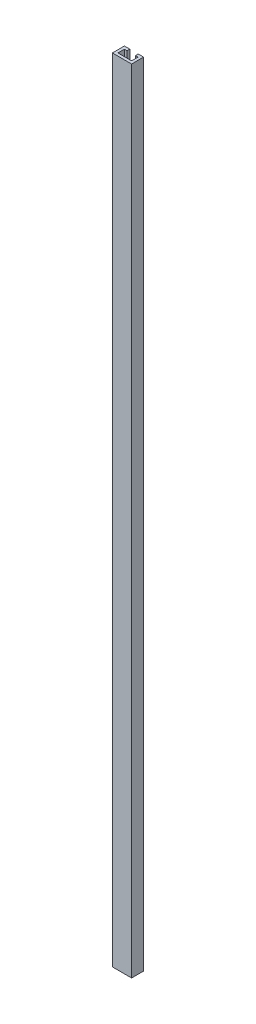
SolidWorks part; units mm, degrees
ref_plane "前视基准面" through (0, 0, 0) normal (0, 0, 1) x (1, 0, 0)
ref_plane "上视基准面" through (0, 0, 0) normal (0, 1, 0) x (1, 0, 0)
ref_plane "右视基准面" through (0, 0, 0) normal (1, 0, 0) x (0, 0, -1)
sketch "草图1" plane through (0, 0, 0) normal (0, 1, 0) x (1, 0, 0)
  line L0 (0, -5) -> (8, -5)
  line L1 (8, -5) -> (8, 0)
  line L2 (8, 0) -> (5.75, 0)
  line L3 (5.75, 0) -> (5.75, -1.15)
  line L4 (5.75, -1.15) -> (6.85, -1.15)
  line L5 (6.85, -1.15) -> (6.85, -3.85)
  line L6 (6.85, -3.85) -> (1.15, -3.85)
  line L7 (1.15, -3.85) -> (1.15, -1.15)
  line L8 (1.15, -1.15) -> (2.25, -1.15)
  line L9 (2.25, -1.15) -> (2.25, 0)
  line L10 (2.25, 0) -> (0, 0)
  line L11 (0, 0) -> (0, -5)
  line L12 (4, -3.85) -> (4, -5) construction
  line L13 (2.25, 0) -> (5.75, 0) construction
  line L14 (4, 0) -> (4, -3.85) construction
  dimension "D1" = 5
  dimension "D2" = 8
  dimension "D3" = 1.15
  dimension "D4" = 1.15
  dimension "D5" = 1.15
  dimension "D6" = 3.5
  dimension "D7" = 5.7
extrude "凸台-拉伸1" add sketch "草图1" along normal blind 330
